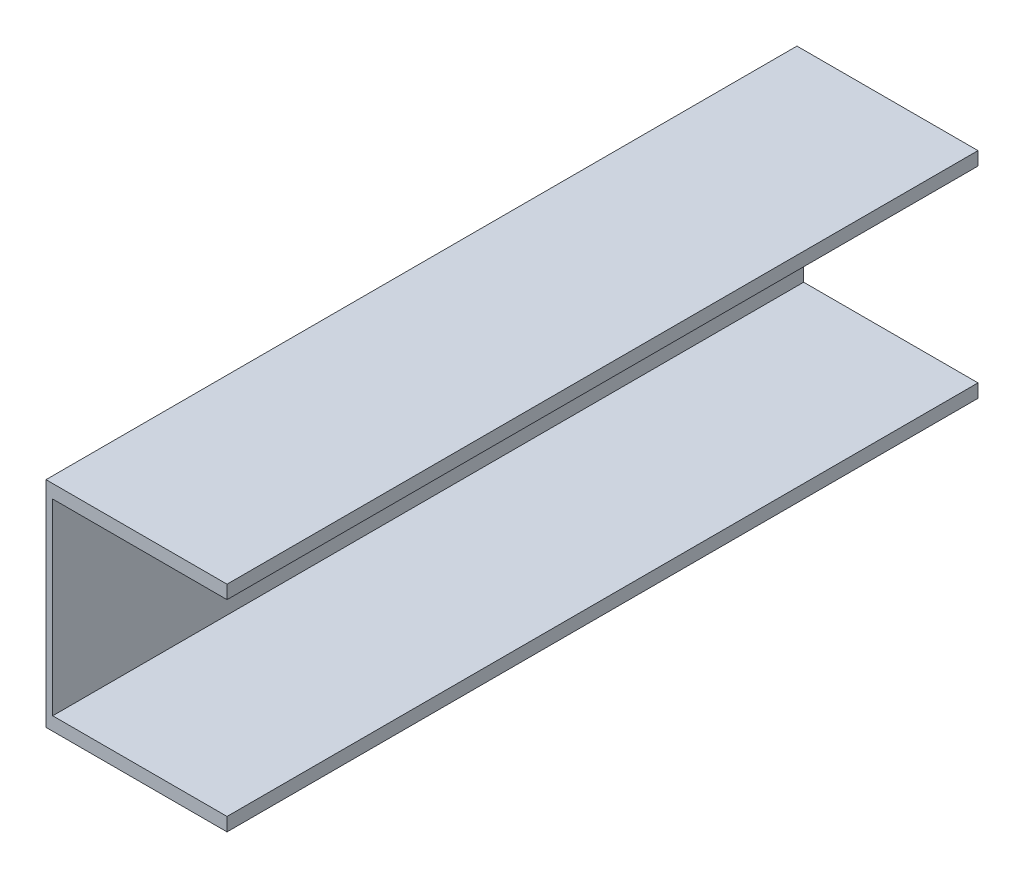
SolidWorks part; units mm, degrees
ref_plane "Front Plane" through (0, 0, 0) normal (0, 0, 1) x (1, 0, 0)
ref_plane "Top Plane" through (0, 0, 0) normal (0, 1, 0) x (1, 0, 0)
ref_plane "Right Plane" through (0, 0, 0) normal (1, 0, 0) x (0, 0, -1)
sketch "Sketch1" plane through (0, 0, 0) normal (1, 0, 0) x (0, 0, -1)
  line L0 (0, 0) -> (355.6, 0)
  line L1 (0, 0) -> (0, 101.6)
  line L2 (0, 101.6) -> (355.6, 101.6)
  line L3 (355.6, 101.6) -> (355.6, 0)
  dimension "D1" = 101.6
  dimension "D2" = 355.6
extrude "Boss-Extrude1" add sketch "Sketch1" along normal blind 3.175
sketch "Sketch2" plane through (3.175, 0, 0) normal (1, 0, 0) x (0, 0, -1)
  line L0 (0, 0) -> (0, 6.35)
  line L1 (0, 101.6) -> (0, 0) construction
  line L2 (0, 6.35) -> (355.6, 6.35)
  line L3 (355.6, 0) -> (355.6, 101.6) construction
  line L4 (355.6, 6.35) -> (355.6, 0)
  line L5 (355.6, 0) -> (0, 0)
  line L6 (0, 101.6) -> (0, 95.25)
  line L7 (0, 95.25) -> (355.6, 95.25)
  line L8 (355.6, 95.25) -> (355.6, 101.6)
  line L9 (355.6, 101.6) -> (0, 101.6)
  dimension "D1" = 6.35
  dimension "D2" = 6.35
extrude "Boss-Extrude2" add sketch "Sketch2" along normal blind 82.55
